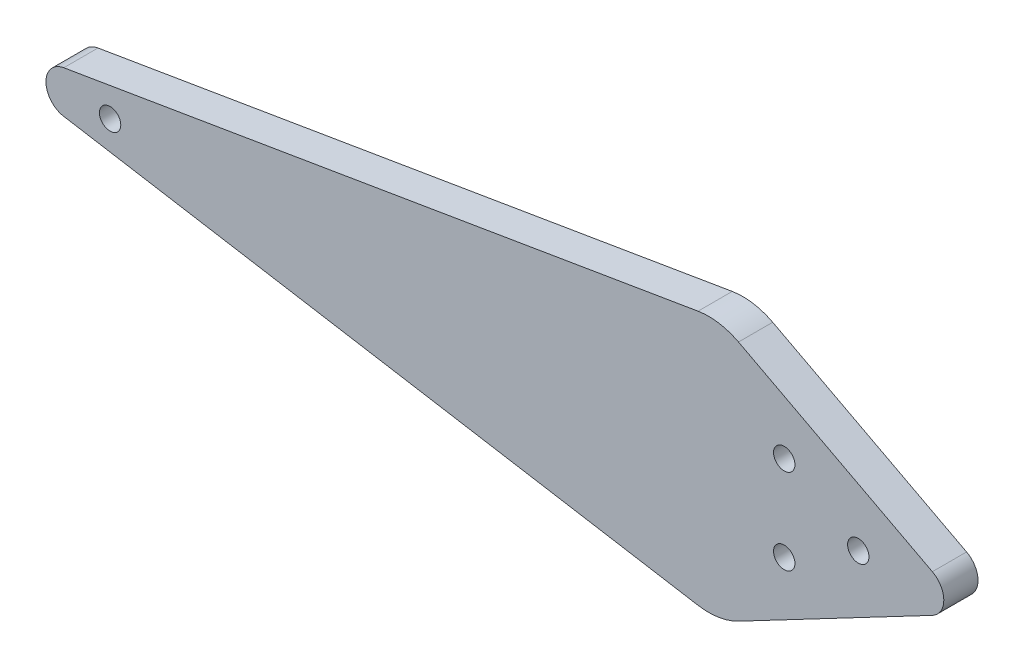
SolidWorks part; units mm, degrees
ref_plane "前视基准面" through (0, 0, 0) normal (0, 0, 1) x (1, 0, 0)
ref_plane "上视基准面" through (0, 0, 0) normal (0, 1, 0) x (1, 0, 0)
ref_plane "右视基准面" through (0, 0, 0) normal (1, 0, 0) x (0, 0, -1)
other "Configuration Table"
sketch "草图1" plane through (0, 0, 0) normal (0, 0, 1) x (1, 0, 0)
  line L0 (-135.209, 0) -> (160.0123, 0) construction
  line L1 (-100.8265, 4.9312) -> (47.5206, 29.7937)
  line L2 (56.9827, 28.2756) -> (102.3276, 4.4252)
  line L3 (-100.8265, -4.9312) -> (47.5206, -29.7937)
  line L4 (56.9827, -28.2756) -> (102.3276, -4.4252)
  line L5 (35.7539, 30) -> (57.6167, 30) construction
  line L6 (30.5447, -30) -> (58.8795, -30) construction
  arc A0 (56.9827, 28.2756) -> (47.5206, 29.7937) centre (50, 15) ccw
  arc A1 (102.3276, -4.4252) -> (102.3276, 4.4252) centre (100, 0) ccw
  arc A2 (-100.8265, 4.9312) -> (-100.8265, -4.9312) centre (-100, 0) ccw
  circle A3 centre (85, 0) radius 2.5
  circle A4 centre (67.6795, 10) radius 2.5
  circle A5 centre (67.6795, -10) radius 2.5
  arc A6 (56.9827, -28.2756) -> (47.5206, -29.7937) centre (50, -15) cw
  circle A7 centre (-90, 0) radius 2.5
  dimension "D1" = 10
  dimension "D2" = 10
  dimension "D3" = 30
  dimension "D6" = 5
  dimension "D7" = 5
  dimension "D12" = 5
  dimension "D4" = 10
  dimension "D5" = 20
  dimension "D8" = 200
  dimension "D9" = 100
  dimension "D10" = 60
  dimension "D11" = 15
  dimension "D13" = 10
  dimension "D14" = 50
extrude "凸台-拉伸1" add sketch "草图1" along normal blind 8
